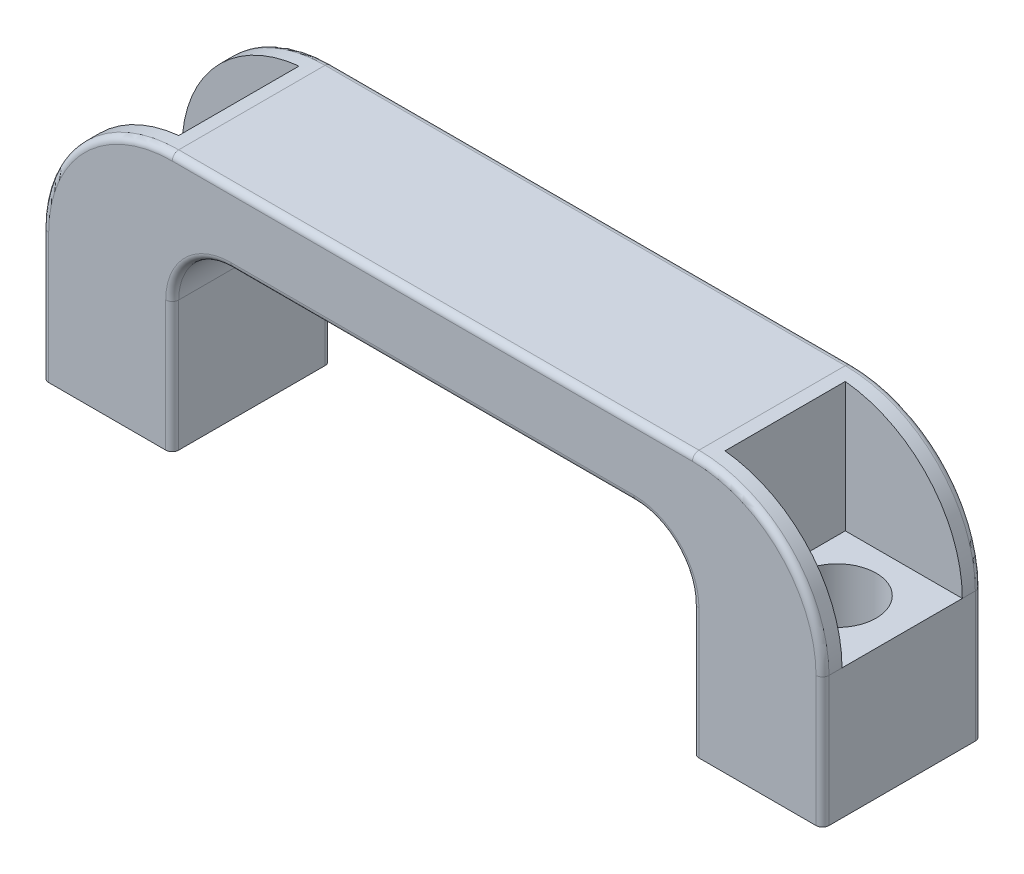
SolidWorks part; units mm, degrees
material "ABS"
ref_plane "Спереди" through (0, 0, 0) normal (0, 0, 1) x (1, 0, 0)
ref_plane "Сверху" through (0, 0, 0) normal (0, 1, 0) x (1, 0, 0)
ref_plane "Справа" through (0, 0, 0) normal (1, 0, 0) x (0, 0, -1)
sketch "Эскиз1" plane through (0, 0, 0) normal (0, 0, 1) x (1, 0, 0)
  line L0 (0, 0) -> (0, 40)
  line L1 (0, 40) -> (120, 40)
  line L2 (120, 40) -> (120, 0)
  line L3 (120, 0) -> (100, 0)
  line L4 (100, 0) -> (100, 29)
  line L5 (100, 29) -> (20, 29)
  line L6 (20, 29) -> (20, 0)
  line L7 (20, 0) -> (0, 0)
  dimension "D1" = 11
  dimension "D2" = 120
  dimension "D3" = 20
  dimension "D4" = 20
  dimension "D5" = 40
extrude "Бобышка-Вытянуть1" add sketch "Эскиз1" along normal blind 24.5
fillet "Скругление1" radius 20 2 edges at (0, 40, 12.25) (120, 40, 12.25)
fillet "Скругление2" radius 9 2 edges at (20, 29, 12.25) (100, 29, 12.25)
sketch "Эскиз2" plane through (120, 0, 0) normal (1, 0, 0) x (0, 0, -1)
  line L0 (0, 20) -> (-24.5, 20) construction
  line L1 (-21.5, 20) -> (-3, 20)
  line L2 (-21.5, 20) -> (-21.5, 46.0601)
  line L3 (-21.5, 46.0601) -> (-3, 46.0601)
  line L4 (-3, 20) -> (-3, 46.0601)
  line L5 (-24.5, 40) -> (-24.5, 20) construction
  line L6 (0, 20) -> (0, 40) construction
  dimension "D1" = 3
  dimension "D2" = 3
extrude "Вырез-Вытянуть1" cut sketch "Эскиз2" against normal blind 18
sketch "Эскиз3" plane through (0, 0, 0) normal (-1, 0, 0) x (0, 0, 1)
  line L0 (24.5, 20) -> (0, 20) construction
  line L1 (3, 20) -> (21.5, 20)
  line L2 (3, 20) -> (3, 41.4871)
  line L3 (3, 41.4871) -> (21.5, 41.4871)
  line L4 (21.5, 20) -> (21.5, 41.4871)
  line L5 (0, 40) -> (0, 20) construction
  line L6 (24.5, 20) -> (24.5, 40) construction
  dimension "D1" = 3
  dimension "D2" = 3
extrude "Вырез-Вытянуть2" cut sketch "Эскиз3" against normal blind 18
fillet "Скругление3" radius 1 20 edges at (20, 10, 24.5) (22.636, 26.364, 24.5) (60, 29, 24.5) (97.364, 26.364, 24.5) (20, 10, 0) (22.636, 26.364, 0) (60, 29, 0) (97.364, 26.364, 0) (120, 10, 24.5) (114.1421, 34.1421, 24.5) (0, 10, 24.5) (5.8579, 34.1421, 24.5) (120, 10, 0) (114.1421, 34.1421, 0) (0, 10, 0) (5.8579, 34.1421, 0) (100, 10, 24.5) (100, 10, 0) (60, 40, 24.5) (60, 40, 0)
sketch "Эскиз6" plane through (0, 0, 0) normal (0, -1, 0) x (-1, 0, 0)
  line L0 (-1, -24.5) -> (-19, -24.5) construction
  line L1 (0, -23.5) -> (0, -1) construction
  line L2 (-101, -24.5) -> (-119, -24.5) construction
  line L4 (-120, -23.5) -> (-120, -1) construction
  circle A0 centre (-10, -12.25) radius 4
  circle A1 centre (-110, -12.25) radius 3.25
  dimension "D1" = 12.25
  dimension "D2" = 8
  dimension "D3" = 10
  dimension "D4" = 6.5
  dimension "D5" = 12.25
  dimension "D6" = 10
extrude "Вырез-Вытянуть3" cut sketch "Эскиз6" against normal through all
sketch "Эскиз7" plane through (0, 20, 0) normal (0, 1, 0) x (1, 0, 0)
  circle A0 centre (10, -12.25) radius 6
  circle A1 centre (110, -12.25) radius 6
  dimension "D1" = 12
  dimension "D2" = 12
extrude "Вырез-Вытянуть4" cut sketch "Эскиз7" against normal blind 10
ref_plane "Плоскость1" through (0, 0, 12.25) normal (0, 0, -1) x (-1, 0, 0)
ref_plane "Плоскость2" through (60, 0, 0) normal (1, 0, 0) x (0, 0, -1)
sketch "Эскиз8" plane through (0, 10, 0) normal (0, 1, 0) x (1, 0, 0)
  circle A0 centre (110, -12.25) radius 3.5
  dimension "D1" = 7
extrude "Вырез-Вытянуть5" cut sketch "Эскиз8" against normal through all
sketch "Эскиз9" plane through (0, 10, 0) normal (0, 1, 0) x (1, 0, 0)
  circle A0 centre (10, -12.25) radius 3.5
  circle A1 centre (10, -12.25) radius 4 construction
  circle A2 centre (10, -12.25) radius 4
  dimension "D1" = 7
extrude "Бобышка-Вытянуть2" add sketch "Эскиз9" against normal up to surface (10 mm away) up to face at (14, 0, 12.25)
